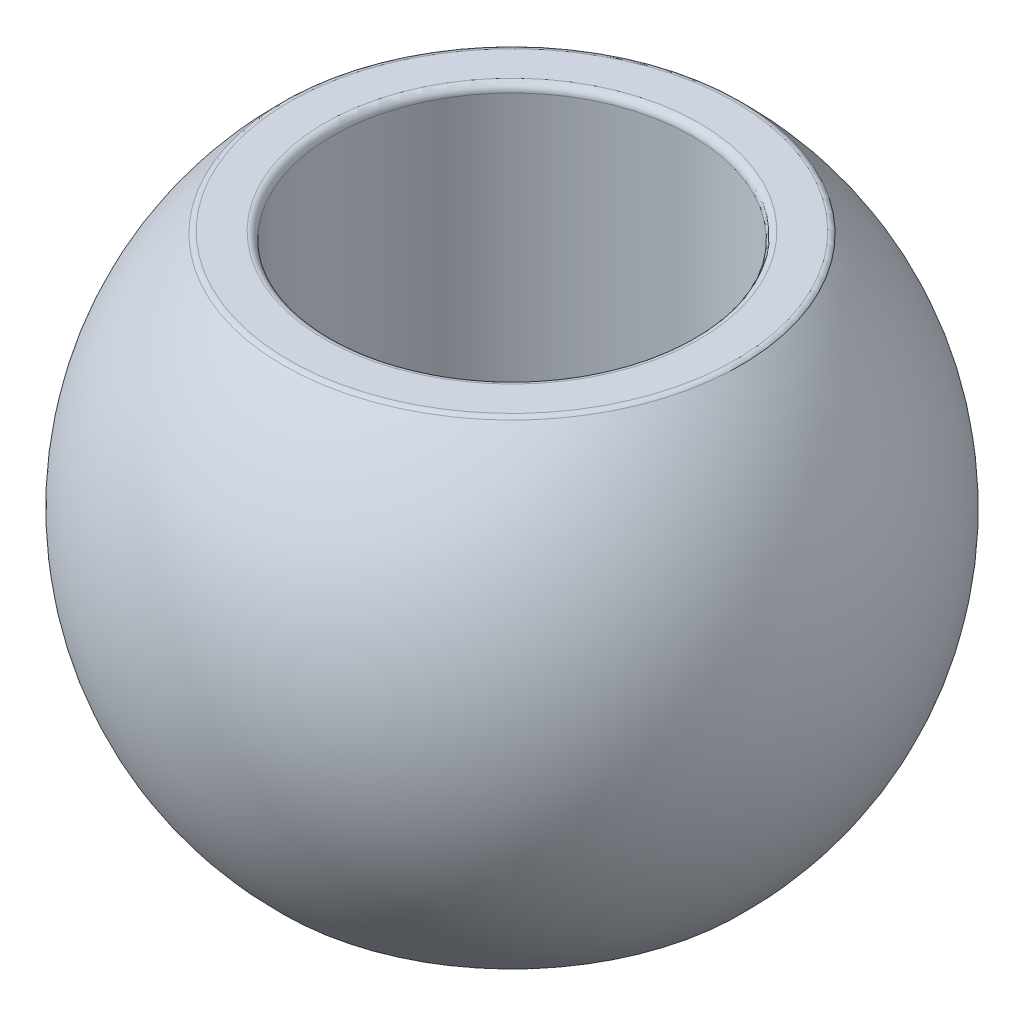
SolidWorks part; units mm, degrees
material "AISI 1015 Steel, Cold Drawn (SS)"
ref_plane "Front Plane" through (0, 0, 0) normal (0, 0, 1) x (1, 0, 0)
ref_plane "Top Plane" through (0, 0, 0) normal (0, 1, 0) x (1, 0, 0)
ref_plane "Right Plane" through (0, 0, 0) normal (1, 0, 0) x (0, 0, -1)
sketch "Sketch1" plane through (0, 0, 0) normal (1, 0, 0) x (0, 0, -1)
  line L0 (0, 11) -> (0, -11) construction
  line L1 (0, -8) -> (7.5498, -8)
  line L2 (0, 8) -> (7.5498, 8)
  line L3 (0, 8) -> (0, -8)
  arc A0 (7.5498, 8) -> (7.5498, -8) centre (0, 0) cw
  dimension "D1" = 22
  dimension "D2" = 11
  dimension "D3" = 8
  dimension "D4" = 8
revolve "Revolve2" add sketch "Sketch1" angle 360 about L0
sketch "Sketch2" plane through (0, 8, 0) normal (0, 1, 0) x (1, 0, 0)
  circle A0 centre (0, 0) radius 6
  dimension "D1" = 12
extrude "Cut-Extrude1" cut sketch "Sketch2" against normal through all
fillet "Fillet1" radius 0.25 4 edges at (0, -8, 7.5498) (0, 8, 7.5498) (0, -8, 6) (0, 8, 6)
